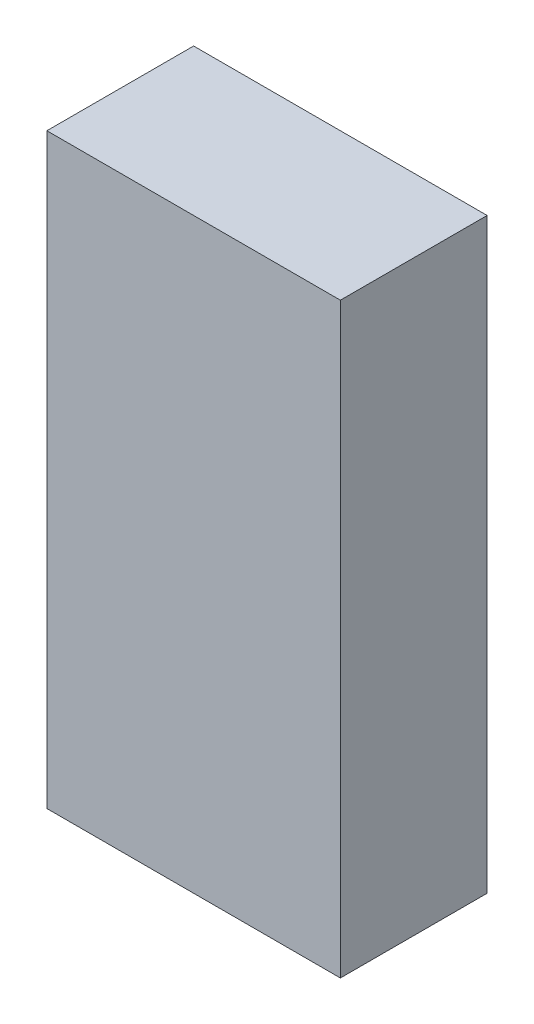
SolidWorks part; units mm, degrees
ref_plane "Plano frontal" through (0, 0, 0) normal (0, 0, 1) x (1, 0, 0)
ref_plane "Plano superior" through (0, 0, 0) normal (0, 1, 0) x (1, 0, 0)
ref_plane "Plano direito" through (0, 0, 0) normal (1, 0, 0) x (0, 0, -1)
sketch "Esboço1" plane through (0, 0, 0) normal (0, 0, 1) x (1, 0, 0)
  line L1 (15, -30) -> (-15, -30)
  line L2 (15, -30) -> (15, 30)
  line L3 (15, 30) -> (-15, 30)
  line L4 (-15, -30) -> (-15, 30)
  line L5 (15, -30) -> (-15, 30) construction
  line L6 (15, 30) -> (-15, -30) construction
  point P0 (0, 0)
  dimension "D1" = 60
  dimension "D2" = 30
extrude "Ressalto-extrusão1" add sketch "Esboço1" along normal mid plane 15
